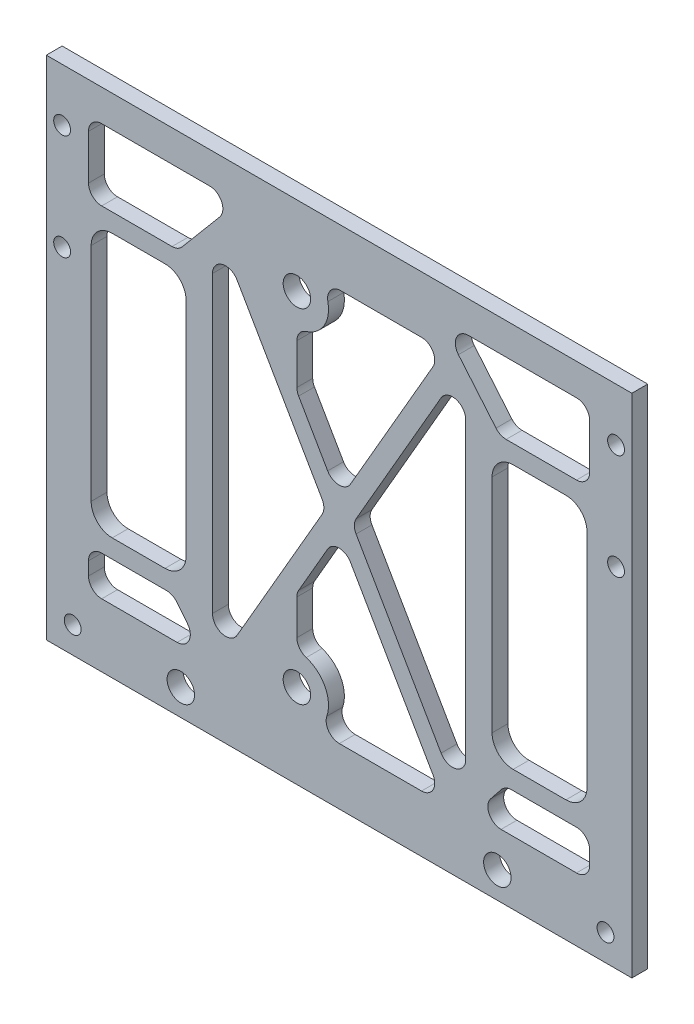
SolidWorks part; units mm, degrees
material "环氧树脂FR-4"
ref_plane "前视基准面" through (0, 0, 0) normal (0, 0, 1) x (1, 0, 0)
ref_plane "上视基准面" through (0, 0, 0) normal (0, 1, 0) x (1, 0, 0)
ref_plane "右视基准面" through (0, 0, 0) normal (1, 0, 0) x (0, 0, -1)
sketch "草图1" plane through (0, 0, 0) normal (0, 0, 1) x (1, 0, 0)
  line L1 (55.5, -48) -> (-55.5, -48)
  line L2 (55.5, -48) -> (55.5, 48)
  line L3 (55.5, 48) -> (-55.5, 48)
  line L4 (-55.5, -48) -> (-55.5, 48)
  line L5 (55.5, -48) -> (-55.5, 48) construction
  line L6 (55.5, 48) -> (-55.5, -48) construction
  point P0 (0, 0)
  dimension "D1" = 111
  dimension "D2" = 96
extrude "凸台-拉伸1" add sketch "草图1" along normal blind 3
sketch "草图2" plane through (0, 0, 3) normal (0, 0, 1) x (1, 0, 0)
  line L0 (-50.5, -43) -> (50.5, -43) construction
  line L1 (0, 0) -> (0, -43) construction
  line L2 (-55.5, -48) -> (55.5, -48) construction
  line L3 (55.5, -48) -> (55.5, 48) construction
  circle A0 centre (-50.5, -43) radius 1.6
  circle A1 centre (50.5, -43) radius 1.6
  dimension "D2" = 3.2
  dimension "D1" = 5
  dimension "D3" = 5
extrude "切除-拉伸1" cut sketch "草图2" against normal through all
sketch "草图3" plane through (0, 0, 3) normal (0, 0, 1) x (1, 0, 0)
  line L0 (0, 0) -> (0, -48) construction
  line L1 (-55.5, -48) -> (55.5, -48) construction
  circle A0 centre (-30, -43) radius 2.6
  circle A1 centre (30, -43) radius 2.6
  dimension "D1" = 60
  dimension "D2" = 5.2
  dimension "D3" = 5
extrude "切除-拉伸2" cut sketch "草图3" against normal through all
sketch "草图4" plane through (0, 0, 3) normal (0, 0, 1) x (1, 0, 0)
  line L0 (-55.5, -48) -> (55.5, -48) construction
  line L1 (-52.5, 38) -> (-52.5, 18) construction
  line L2 (-55.5, 48) -> (-55.5, -48) construction
  line L3 (0, 0) -> (0, -48) construction
  circle A0 centre (-52.5, 18) radius 1.6
  circle A1 centre (-52.5, 38) radius 1.6
  circle A2 centre (52.5, 38) radius 1.6
  circle A3 centre (52.5, 18) radius 1.6
  dimension "D1" = 66
  dimension "D3" = 3.2
  dimension "D2" = 20
  dimension "D4" = 3
extrude "切除-拉伸3" cut sketch "草图4" against normal through all
sketch "草图8" plane through (0, 0, 3) normal (0, 0, 1) x (1, 0, 0)
  line L0 (-8, 0) -> (-8, -48) construction
  line L1 (-55.5, -48) -> (55.5, -48) construction
  circle A2 centre (-8, -32) radius 2.6
  circle A3 centre (-8, 33) radius 2.6
  dimension "D1" = 65
  dimension "D2" = 5.2
  dimension "D3" = 16
  dimension "D4" = 8
extrude "切除-拉伸10" cut sketch "草图8" against normal through all
sketch "草图5" plane through (0, 0, 3) normal (0, 0, 1) x (1, 0, 0)
  line L0 (-47, 25) -> (-47, -25)
  line L1 (-47, -25) -> (-29, -25)
  line L2 (-29, -25) -> (-29, 25)
  line L3 (-29, 25) -> (-47, 25)
  line L4 (55.5, 48) -> (-55.5, 48) construction
  line L5 (0, 0) -> (0, -48) construction
  line L6 (-55.5, -48) -> (55.5, -48) construction
  line L7 (29, -25) -> (29, 25)
  line L8 (47, -25) -> (29, -25)
  line L9 (47, 25) -> (47, -25)
  line L10 (29, 25) -> (47, 25)
  dimension "D1" = 29
  dimension "D2" = 18
  dimension "D3" = 50
  dimension "D4" = 23
extrude "切除-拉伸4" cut sketch "草图5" against normal through all
fillet "圆角1" radius 4 8 edges at (29, 25, 1.5) (47, 25, 1.5) (47, -25, 1.5) (29, -25, 1.5) (-47, 25, 1.5) (-29, 25, 1.5) (-29, -25, 1.5) (-47, -25, 1.5)
sketch "草图6" plane through (0, 0, 3) normal (0, 0, 1) x (1, 0, 0)
  line L0 (0, 48) -> (0, -48) construction
  line L1 (-8, 33) -> (-8, 16.5263)
  line L4 (55.5, 48) -> (-55.5, 48) construction
  line L5 (-8, -32) -> (-14.7003, -28.1316)
  line L16 (-8, -26) -> (-8, -16.5263)
  line L17 (-55.5, -48) -> (55.5, -48) construction
  line L18 (-29, 0) -> (29, 0) construction
  line L19 (-29, -21) -> (-29, 21) construction
  line L20 (29, 21) -> (29, -21) construction
  line L21 (-24, 37.2391) -> (-2.5, 0)
  line L22 (-24, 37.2391) -> (-24, -37.2391)
  line L23 (-19.9585, 37.2391) -> (0, 2.6699)
  line L24 (-19.9585, 37.2391) -> (19.9585, 37.2391)
  line L25 (19.9585, 37.2391) -> (0, 2.6699)
  line L26 (24, 37.2391) -> (24, -37.2391)
  line L27 (24, 37.2391) -> (2.5, 0)
  line L28 (24, -37.2391) -> (2.5, 0)
  line L29 (19.9585, -37.2391) -> (0, -2.6699)
  line L30 (-19.9585, -37.2391) -> (19.9585, -37.2391)
  line L31 (-19.9585, -37.2391) -> (0, -2.6699)
  line L32 (-24, -37.2391) -> (-2.5, 0)
  circle A0 centre (-8, -32) radius 6
  circle A1 centre (-8, 33) radius 6
  point P16 (0, -37.2391)
  point P21 (0, 37.2391)
  point P25 (24, 0)
  point P29 (-24, 0)
  dimension "D5" = 12
  dimension "D1" = 5
  dimension "D2" = 3.5
  dimension "D3" = 30
  dimension "D4" = 5
extrude "切除-拉伸8" cut sketch "草图6" against normal through all contours L22 L32 L21 | A1 L24 L23 L25 | L28 L26 L27 | A0 L30 L29 L31
fillet "圆角2" radius 2.5 16 edges at (-2.5, 0, 1.5) (-24, 37.2391, 1.5) (0, -2.6699, 1.5) (19.9585, -37.2391, 1.5) (0, 2.6699, 1.5) (19.9585, 37.2391, 1.5) (24, -37.2391, 1.5) (2.5, 0, 1.5) (24, 37.2391, 1.5) (-24, -37.2391, 1.5) (-8, -26, 1.5) (-8, -16.5263, 1.5) (-3.7538, 37.2391, 1.5) (-8, 16.5263, 1.5) (-8, 27, 1.5) (-5.0756, -37.2391, 1.5)
sketch "草图7" plane through (0, 0, 3) normal (0, 0, 1) x (1, 0, 0)
  line L0 (-47.5, 38) -> (-47.5, 28.5)
  line L1 (-47.5, 28.5) -> (-30.5, 28.5)
  line L2 (-30.5, 28.5) -> (-19.1722, 42)
  line L3 (-19.1722, 42) -> (-47.5, 42)
  line L4 (-47.5, 42) -> (-47.5, 38)
  line L5 (-33, 25) -> (-43, 25) construction
  line L6 (55.5, 48) -> (-55.5, 48) construction
  line L7 (0, 0) -> (0, 48) construction
  line L8 (19.1722, 42) -> (47.5, 42)
  line L9 (30.5, 28.5) -> (19.1722, 42)
  line L10 (47.5, 28.5) -> (30.5, 28.5)
  line L11 (47.5, 38) -> (47.5, 28.5)
  line L12 (47.5, 42) -> (47.5, 38)
  line L13 (-47.5, -28.5) -> (-31.5, -28.5)
  line L14 (-31.5, -28.5) -> (-25.5, -36)
  line L15 (-25.5, -36) -> (-47.5, -36)
  line L16 (-47.5, -36) -> (-47.5, -28.5)
  line L17 (-55.5, 48) -> (-55.5, -48) construction
  line L18 (-55.5, -48) -> (55.5, -48) construction
  line L19 (-43, -25) -> (-33, -25) construction
  line L20 (25.5, -36) -> (47.5, -36)
  line L21 (31.5, -28.5) -> (25.5, -36)
  line L22 (47.5, -28.5) -> (31.5, -28.5)
  line L23 (47.5, -36) -> (47.5, -28.5)
  circle A0 centre (-52.5, 38) radius 5
  point P10 (-38, 25)
  dimension "D1" = 10
  dimension "D2" = 3.5
  dimension "D3" = 130
  dimension "D4" = 6
  dimension "D5" = 17
  dimension "D6" = 8
  dimension "D7" = 12
  dimension "D8" = 3.5
  dimension "D9" = 16
  dimension "D10" = 22
extrude "切除-拉伸9" cut sketch "草图7" against normal through all contours L3 L4 L0 L1 L2 | L16 L15 L14 L13 | L20 L23 L22 L21 | L12 L8 L9 L10 L11
fillet "圆角3" radius 2.5 16 edges at (47.5, 28.5, 1.5) (30.5, 28.5, 1.5) (19.1722, 42, 1.5) (47.5, 42, 1.5) (31.5, -28.5, 1.5) (47.5, -28.5, 1.5) (47.5, -36, 1.5) (25.5, -36, 1.5) (-30.5, 28.5, 1.5) (-47.5, 28.5, 1.5) (-47.5, 42, 1.5) (-19.1722, 42, 1.5) (-47.5, -28.5, 1.5) (-31.5, -28.5, 1.5) (-25.5, -36, 1.5) (-47.5, -36, 1.5)
